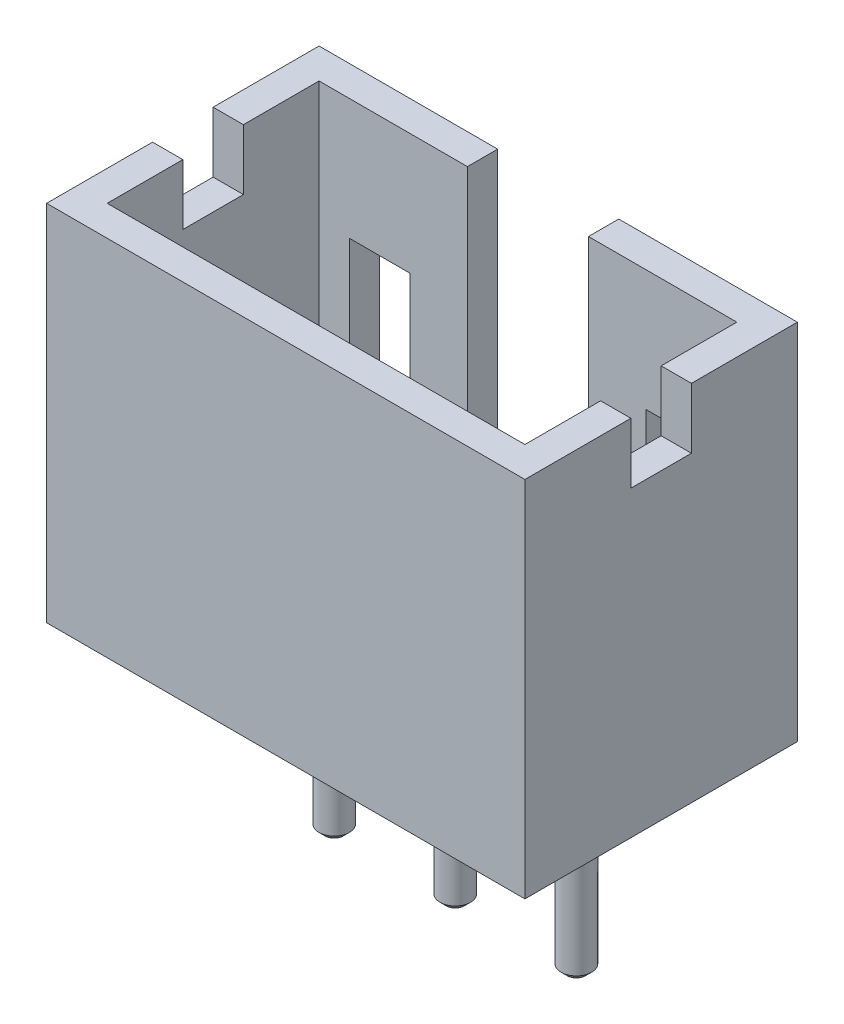
SolidWorks part; units mm, degrees
ref_plane "Alzado" through (0, 0, 0) normal (0, 0, 1) x (1, 0, 0)
ref_plane "Planta" through (0, 0, 0) normal (0, 1, 0) x (1, 0, 0)
ref_plane "Vista lateral" through (0, 0, 0) normal (1, 0, 0) x (0, 0, -1)
sketch "Croquis1" plane through (0, 0, 0) normal (0, 1, 0) x (1, 0, 0)
  line L1 (-3.95, 1.7) -> (3.95, 1.7)
  line L2 (-3.95, 1.7) -> (-3.95, -2.8)
  line L3 (-3.95, -2.8) -> (3.95, -2.8)
  line L4 (3.95, 1.7) -> (3.95, -2.8)
  point P6 (0, 0)
  point P12 (0, 0)
  point P13 (0, 0)
  dimension "D1" = 7.9
  dimension "D2" = 4.5
extrude "Saliente-Extruir2" add sketch "Croquis1" along normal blind 6 contours L2 L1 L4 L3
sketch "Croquis4" plane through (0, 6, 0) normal (0, 1, 0) x (1, 0, 0)
  line L8 (-3.45, 1.2) -> (3.45, 1.2)
  line L9 (-3.45, 1.2) -> (-3.45, -2.3)
  line L10 (-3.45, -2.3) -> (3.45, -2.3)
  line L11 (3.45, 1.2) -> (3.45, -2.3)
  point P0 (0, 0)
  point P6 (0, -0.55)
  dimension "D1" = 6.9
  dimension "D2" = 3.5
extrude "Cortar-Extruir2" cut sketch "Croquis4" against normal blind 5 contours L9 L8 L11 L10
sketch "Croquis5" plane through (0, 0, 0) normal (0, -1, 0) x (-1, 0, 0)
  line L0 (3.95, 1.7) -> (-3.95, 1.7) construction
  circle A0 centre (0, 0) radius 0.25
  circle A1 centre (-2, 0) radius 0.25
  circle A2 centre (2, 0) radius 0.25
  point P4 (0, 1.7)
  point P5 (0, 0)
  dimension "D2" = 2
  dimension "D4" = 0.5
  dimension "D5" = 0.5
  dimension "D6" = 0.5
  dimension "D1" = 1.7
  dimension "D3" = 2
extrude "Saliente-Extruir3" add sketch "Croquis5" along normal mid plane 6.8
sketch "Croquis6" plane through (0, 6, 0) normal (0, 1, 0) x (1, 0, 0)
  line L0 (0, 1.7) -> (0, -2.8) construction
  line L1 (-3.95, 1.7) -> (3.95, 1.7) construction
  line L2 (-3.95, -2.8) -> (3.95, -2.8) construction
  line L4 (-1, 1.7) -> (1, 1.7)
  line L5 (-1, 1.7) -> (-1, 1.2)
  line L6 (-1, 1.2) -> (1, 1.2)
  line L7 (1, 1.7) -> (1, 1.2)
  line L8 (-1, 1.7) -> (1, 1.2) construction
  line L9 (-1, 1.2) -> (1, 1.7) construction
  point P6 (0, 1.45)
  dimension "D1" = 2
  dimension "D2" = 0.5
extrude "Cortar-Extruir3" cut sketch "Croquis6" against normal blind 5 contours L5 L4 L7 L6
sketch "Croquis7" plane through (3.95, 0, 0) normal (1, 0, 0) x (0, 0, -1)
  line L0 (-0.55, 6) -> (-0.55, 0) construction
  line L1 (1.7, 6) -> (-2.8, 6) construction
  line L2 (1.7, 0) -> (-2.8, 0) construction
  line L4 (-1.05, 6) -> (-0.05, 6)
  line L5 (-1.05, 6) -> (-1.05, 5)
  line L6 (-1.05, 5) -> (-0.05, 5)
  line L7 (-0.05, 6) -> (-0.05, 5)
  line L8 (-1.05, 6) -> (-0.05, 5) construction
  line L9 (-1.05, 5) -> (-0.05, 6) construction
  point P6 (-0.55, 5.5)
  dimension "D1" = 1
  dimension "D2" = 1
extrude "Cortar-Extruir5" cut sketch "Croquis7" against normal blind 8 contours L5 L4 L7 L6
sketch "Croquis8" plane through (0, 0, -1.7) normal (0, 0, -1) x (-1, 0, 0)
  line L0 (3.95, 0) -> (-3.95, 0) construction
  line L1 (-2.95, 0) -> (-1.95, 0)
  line L2 (-2.95, 0) -> (-2.95, 4.0005)
  line L3 (-2.95, 4.0005) -> (-1.95, 4.0005)
  line L4 (-1.95, 0) -> (-1.95, 4.0005)
  line L5 (-3.95, 6) -> (-3.95, 0) construction
  line L6 (0, 0) -> (0, 6) construction
  line L7 (3.45, 6) -> (-3.45, 6) construction
  line L8 (2.95, 4.0005) -> (1.95, 4.0005)
  line L9 (1.95, 0) -> (1.95, 4.0005)
  line L10 (2.95, 0) -> (1.95, 0)
  line L11 (2.95, 0) -> (2.95, 4.0005)
  line M15 (-3.95, 0) -> (3.95, 0)
  dimension "D1" = 1
  dimension "D2" = 1
extrude "Cortar-Extruir7" cut sketch "Croquis8" against normal blind 0.5 contours L4 L3 L2 M15 | L8 L9 L10 L11
chamfer "Chaflán3" distance 0.1 angle 45 6 edges at (-2, -3.4, -0.25) (0, -3.4, -0.25) (2, -3.4, -0.25) (-2, 3.4, -0.25) (0, 3.4, -0.25) (2, 3.4, -0.25)
